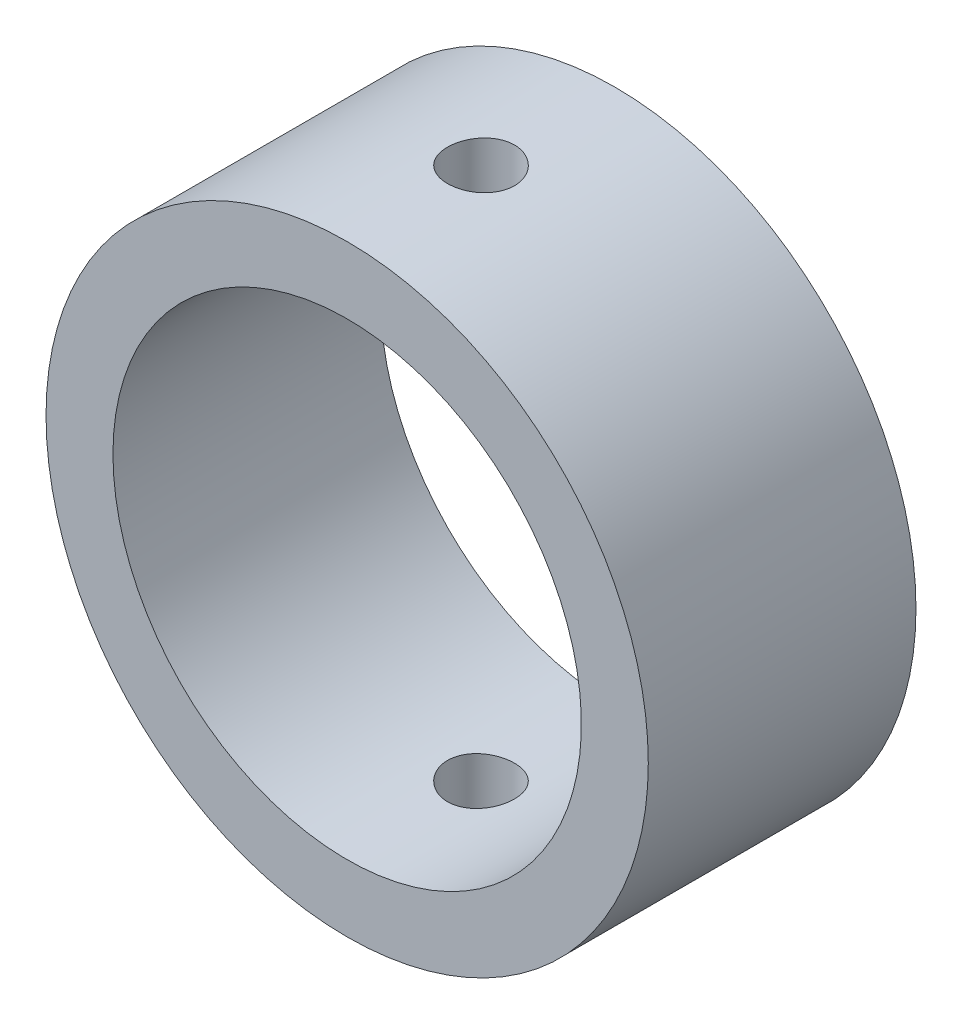
SolidWorks part; units mm, degrees
ref_plane "Front Plane" through (0, 0, 0) normal (0, 0, 1) x (1, 0, 0)
ref_plane "Top Plane" through (0, 0, 0) normal (0, 1, 0) x (1, 0, 0)
ref_plane "Right Plane" through (0, 0, 0) normal (1, 0, 0) x (0, 0, -1)
sketch "Sketch1" plane through (0, 0, 0) normal (0, 1, 0) x (1, 0, 0)
  line L0 (571.5, 0) -> (0, 0)
  line L1 (0, 0) -> (0, -508)
  line L2 (0, -508) -> (571.5, -508)
  line L3 (571.5, -508) -> (571.5, 0)
  line L4 (0, 0) -> (0, -508) construction
  dimension "D1" = 508
revolve "Revolve1" add sketch "Sketch1" angle 360 about L4
hole_wizard "Hole1" positions "Sketch3" profile "Sketch2" legacy
sketch "Sketch3" plane through (0, 0, 0) normal (0, 0, -1) x (-1, 0, 0)
  point P0 (0, 0)
sketch "Sketch2" plane through (0, 0, 0) normal (1, 0, 0) x (0, 1, 0)
  line L0 (0, 0) -> (0, 508)
  line L1 (0, 508) -> (444.5, 508)
  line L2 (444.5, 508) -> (444.5, 0)
  line L3 (444.5, 0) -> (0, 0)
  line L4 (0, 110) -> (0, -10) construction
  dimension "Diameter" = 889
  dimension "Depth" = 508
ref_plane "Plane1" through (0, -439.9409, 0) normal (0, 1, 0) x (1, 0, 0)
hole_wizard "Hole2" positions "Sketch5" profile "Sketch4" legacy
sketch "Sketch5" plane through (0, -439.9409, 0) normal (0, 1, 0) x (1, 0, 0)
  point P0 (0, -254)
sketch "Sketch4" plane through (0, -439.9409, 254) normal (1, 0, 0) x (0, 0, 1)
  line L0 (0, 0) -> (0, 131.5591)
  line L1 (0, 131.5591) -> (63.5, 131.5591)
  line L2 (63.5, 131.5591) -> (63.5, 0)
  line L3 (63.5, 0) -> (0, 0)
  line L4 (0, 110) -> (0, -10) construction
  dimension "Diameter" = 127
  dimension "Depth" = 131.5591
ref_plane "Plane2" through (0, 439.9409, 0) normal (0, -1, 0) x (-1, 0, 0)
hole_wizard "Hole3" positions "Sketch7" profile "Sketch6" legacy
sketch "Sketch7" plane through (0, 439.9409, 0) normal (0, -1, 0) x (-1, 0, 0)
  line L0 (444.5, 0) -> (-444.5, 0) construction
  circle A0 centre (0, -254) radius 63.5 construction
  point P0 (0, -254)
sketch "Sketch6" plane through (0, 439.9409, 254) normal (1, 0, 0) x (0, 0, -1)
  line L0 (0, 0) -> (0, 131.5591)
  line L1 (0, 131.5591) -> (63.5, 131.5591)
  line L2 (63.5, 131.5591) -> (63.5, 0)
  line L3 (63.5, 0) -> (0, 0)
  line L4 (0, 110) -> (0, -10) construction
  dimension "Diameter" = 127
  dimension "Depth" = 131.5591
